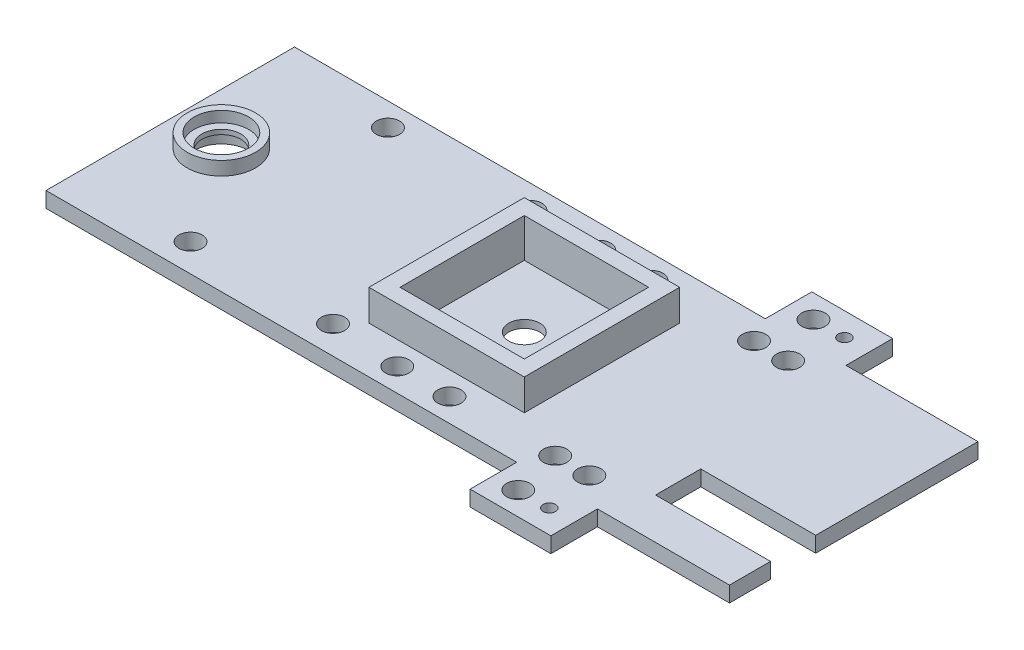
SolidWorks part; units mm, degrees
ref_plane "Front Plane" through (0, 0, 0) normal (0, 0, 1) x (1, 0, 0)
ref_plane "Top Plane" through (0, 0, 0) normal (0, 1, 0) x (1, 0, 0)
ref_plane "Right Plane" through (0, 0, 0) normal (1, 0, 0) x (0, 0, -1)
sketch "Sketch1" plane through (0, 0, 0) normal (0, 1, 0) x (1, 0, 0)
  line L1 (-279.4, -50.8) -> (0, -50.8)
  line L2 (-279.4, -50.8) -> (-279.4, 50.8)
  line L3 (-279.4, 50.8) -> (0, 50.8)
  line L4 (0, -50.8) -> (0, 50.8)
  point P0 (0, 0)
  dimension "D1" = 279.4
  dimension "D2" = 101.6
  dimension "D3" = 50.8
extrude "Boss-Extrude1" add sketch "Sketch1" along normal blind 6.35
sketch "Sketch2" plane through (0, 6.35, 0) normal (0, 1, 0) x (1, 0, 0)
  line L0 (-279.4, 50.8) -> (-279.4, -50.8) construction
  line L2 (0, 50.8) -> (-279.4, 50.8) construction
  circle A0 centre (-258.5106, 0) radius 13.97
  dimension "D1" = 50.8
  dimension "D2" = 27.94
  dimension "D3" = 20.8894
extrude "Boss-Extrude3" add sketch "Sketch2" along normal blind 5.5562
sketch "Sketch9" plane through (0, 11.9062, 0) normal (0, 1, 0) x (1, 0, 0)
  circle A0 centre (-258.5106, 0) radius 11.1125
  dimension "D1" = 22.225
extrude "Cut-Extrude4" cut sketch "Sketch9" against normal blind 4.445
sketch "Sketch10" plane through (0, 0, 0) normal (0, -1, 0) x (-1, 0, 0)
  circle A0 centre (258.5106, 0) radius 11.1125
  dimension "D1" = 22.225
extrude "Cut-Extrude5" cut sketch "Sketch10" against normal blind 5.5562
sketch "Sketch11" plane through (0, 7.4613, 0) normal (0, 1, 0) x (1, 0, 0)
  circle A0 centre (-258.5106, 0) radius 7.9375
  dimension "D1" = 15.875
extrude "Cut-Extrude6" cut sketch "Sketch11" against normal through all
sketch "Sketch12" plane through (0, 6.35, 0) normal (0, 1, 0) x (1, 0, 0)
  line L0 (0, 50.8) -> (-279.4, 50.8) construction
  line L1 (-279.4, 50.8) -> (-279.4, -50.8) construction
  circle A0 centre (-134.6662, 0) radius 6.35
  dimension "D1" = 12.7
  dimension "D2" = 50.8
  dimension "D3" = 144.7338
extrude "Cut-Extrude7" cut sketch "Sketch12" against normal through all
sketch "Sketch22" plane through (0, 6.35, 0) normal (0, 1, 0) x (1, 0, 0)
  line L1 (-102.9162, -31.75) -> (-166.4162, -31.75)
  line L2 (-102.9162, -31.75) -> (-102.9162, 31.75)
  line L3 (-102.9162, 31.75) -> (-166.4162, 31.75)
  line L4 (-166.4162, -31.75) -> (-166.4162, 31.75)
  line L5 (-102.9162, -31.75) -> (-166.4162, 31.75) construction
  line L6 (-102.9162, 31.75) -> (-166.4162, -31.75) construction
  circle A0 centre (-134.6662, 0) radius 6.35 construction
  point P0 (-134.6662, 0)
  dimension "D1" = 63.5
  dimension "D2" = 63.5
extrude "Boss-Extrude7" add sketch "Sketch22" along normal blind 12.7
sketch "Sketch25" plane through (0, 19.05, 0) normal (0, 1, 0) x (1, 0, 0)
  line L1 (-109.2662, -25.4) -> (-160.0662, -25.4)
  line L2 (-109.2662, -25.4) -> (-109.2662, 25.4)
  line L3 (-109.2662, 25.4) -> (-160.0662, 25.4)
  line L4 (-160.0662, -25.4) -> (-160.0662, 25.4)
  line L5 (-109.2662, -25.4) -> (-160.0662, 25.4) construction
  line L6 (-109.2662, 25.4) -> (-160.0662, -25.4) construction
  circle A0 centre (-134.6662, 0) radius 6.35 construction
  point P0 (-134.6662, 0)
  dimension "D1" = 50.8
  dimension "D2" = 50.8
extrude "Cut-Extrude11" cut sketch "Sketch25" against normal blind 15.875
sketch "Sketch32" plane through (0, 6.35, 0) normal (0, 1, 0) x (1, 0, 0)
  line L0 (0, -50.8) -> (0, 50.8) construction
  line L3 (-279.4, -50.8) -> (0, -50.8) construction
  line L5 (0, 50.8) -> (-279.4, 50.8) construction
  circle A0 centre (-67.442, -40.64) radius 4.7625
  circle A1 centre (-81.412, -40.64) radius 4.7625
  circle A2 centre (-67.442, 40.64) radius 4.7625
  circle A3 centre (-81.412, 40.64) radius 4.7625
  dimension "D1" = 10.16
  dimension "D2" = 10.16
  dimension "D3" = 10.16
  dimension "D4" = 10.16
  dimension "D9" = 9.525
  dimension "D10" = 9.525
  dimension "D11" = 9.525
  dimension "D12" = 9.525
  dimension "D5" = 13.97
  dimension "D6" = 13.97
  dimension "D7" = 81.28
  dimension "D8" = 81.412
extrude "Cut-Extrude12" cut sketch "Sketch32" against normal blind 6.35
sketch "Sketch38" plane through (0, 6.35, 0) normal (0, 1, 0) x (1, 0, 0)
  line L0 (0, -50.8) -> (0, 50.8) construction
  line L1 (0, -34.0128) -> (-46.99, -34.0128)
  line L2 (0, -34.0128) -> (0, -15.5426)
  line L3 (0, -15.5426) -> (-46.99, -15.5426)
  line L4 (-46.99, -34.0128) -> (-46.99, -15.5426)
  line L6 (-279.4, -50.8) -> (0, -50.8) construction
  dimension "D1" = 35.2574
  dimension "D2" = 18.4703
  dimension "D3" = 46.99
extrude "Cut-Extrude13" cut sketch "Sketch38" against normal blind 6.35
sketch "Sketch60" plane through (0, 6.35, 0) normal (0, 1, 0) x (1, 0, 0)
  line L1 (-279.4, 50.8) -> (-279.4, -50.8) construction
  line L2 (0, 50.8) -> (-279.4, 50.8) construction
  circle A0 centre (-231.7492, 41.3241) radius 4.7625
  circle A1 centre (-231.7492, -39.3693) radius 4.7625
  circle A2 centre (-173.5092, -39.3693) radius 4.7625
  circle A3 centre (-173.5092, 41.3241) radius 4.7625
  dimension "D1" = 47.6508
  dimension "D5" = 9.525
  dimension "D6" = 9.525
  dimension "D7" = 9.525
  dimension "D8" = 9.525
  dimension "D2" = 58.24
  dimension "D3" = 80.6935
  dimension "D4" = 9.4759
  dimension "D9" = 105.8908
extrude "Cut-Extrude23" cut sketch "Sketch60" against normal up to surface (6.35 mm away) up to face at (-81.5975, 0, 12.3889)
sketch "Sketch64" plane through (0, 6.35, 0) normal (0, 1, 0) x (1, 0, 0)
  line L0 (-279.4, -50.8) -> (0, -50.8) construction
  circle A0 centre (-145.3342, -41.275) radius 4.7625
  circle A1 centre (-123.9982, -41.275) radius 4.7625
  circle A3 centre (-134.6662, 0) radius 6.35 construction
  dimension "D1" = 21.336
  dimension "D3" = 9.525
  dimension "D4" = 9.525
  dimension "D2" = 10.668
  dimension "D5" = 9.525
  dimension "D6" = 9.525
extrude "Cut-Extrude24" cut sketch "Sketch64" against normal through all
mirror "Mirror1" about plane through (0, 0, 0) normal (0, 0, 1) of "Cut-Extrude24"
sketch "Sketch69" plane through (0, 0, 50.8) normal (0, 0, 1) x (1, 0, 0)
  line L0 (-279.4, 6.35) -> (0, 6.35) construction
  line L1 (-86.9754, 6.35) -> (-53.9554, 6.35)
  line L2 (-86.9754, 6.35) -> (-86.9754, 0)
  line L3 (-86.9754, 0) -> (-53.9554, 0)
  line L4 (-53.9554, 6.35) -> (-53.9554, 0)
  line L5 (-279.4, 0) -> (0, 0) construction
  line L7 (0, 6.35) -> (0, 0) construction
  point P8 (0, 0)
  dimension "D1" = 33.02
  dimension "D2" = 53.9554
extrude "Boss-Extrude10" add sketch "Sketch69" along normal blind 19.05
sketch "Sketch70" plane through (0, 6.35, 0) normal (0, 1, 0) x (1, 0, 0)
  line L1 (-86.9754, -69.85) -> (-86.9754, -50.8) construction
  circle A0 centre (-76.8154, -60.325) radius 4.7625
  circle A1 centre (-64.1154, -60.325) radius 2.54
  point P2 (0, 0)
  point P6 (-86.9754, -60.325)
  dimension "D1" = 9.525
  dimension "D3" = 5.08
  dimension "D2" = 10.16
  dimension "D4" = 22.86
extrude "Cut-Extrude26" cut sketch "Sketch70" against normal up to surface (6.35 mm away) up to face at (-145.3342, 0, -46.0375)
mirror "Mirror2" about plane through (0, 0, 0) normal (0, 0, 1) of "Cut-Extrude26", "Boss-Extrude10"
